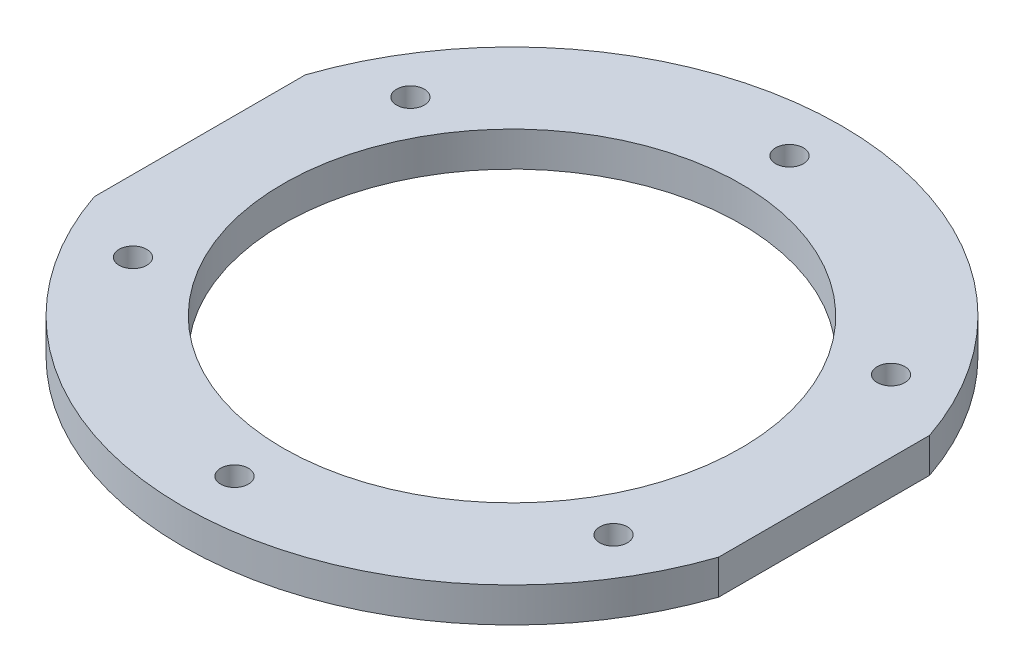
SolidWorks part; units mm, degrees
material "Сосна"
ref_plane "Спереди" through (0, 0, 0) normal (0, 0, 1) x (1, 0, 0)
ref_plane "Сверху" through (0, 0, 0) normal (0, 1, 0) x (1, 0, 0)
ref_plane "Справа" through (0, 0, 0) normal (1, 0, 0) x (0, 0, -1)
sketch "Эскиз1" plane through (0, 0, 0) normal (0, 1, 0) x (1, 0, 0)
  circle A0 centre (0, 0) radius 47.5
  circle A1 centre (0, 0) radius 33
  dimension "D1" = 66
  dimension "D2" = 95
extrude "Бобышка-Вытянуть1" add sketch "Эскиз1" along normal blind 5
sketch "Эскиз2" plane through (0, 0, 0) normal (0, 0, 1) x (1, 0, 0)
  line L0 (-45, -5) -> (45, -5) construction
  line L1 (-55, 15) -> (-45, 15)
  line L2 (-55, 15) -> (-55, -5)
  line L3 (-55, -5) -> (-45, -5)
  line L4 (-45, 15) -> (-45, -5)
  line L5 (55, 15) -> (45, 15)
  line L6 (55, 15) -> (55, -5)
  line L7 (55, -5) -> (45, -5)
  line L8 (45, 15) -> (45, -5)
  line L9 (0, 0) -> (0, -5) construction
  dimension "D1" = 90
  dimension "D2" = 10
  dimension "D3" = 10
  dimension "D4" = 20
  dimension "D5" = 5
extrude "Вырез-Вытянуть1" cut sketch "Эскиз2" against normal mid plane 50
sketch "Эскиз3" plane through (0, 0, 0) normal (0, 1, 0) x (1, 0, 0)
  line L0 (0, 0) -> (0, 40) construction
  line L1 (0, 0) -> (-45, 0) construction
  line L2 (-45, -15.2069) -> (-45, 15.2069) construction
  circle A0 centre (0, 40) radius 2
  circle A1 centre (0, -40) radius 2
  dimension "D1" = 4
  dimension "D2" = 40
extrude "Вырез-Вытянуть2" cut sketch "Эскиз3" against normal mid plane 50
pattern_circular "Круговой массив1" count 3 over 360 about axis through (0, 0, 0) along (0, 1, 0) of "Вырез-Вытянуть2"
